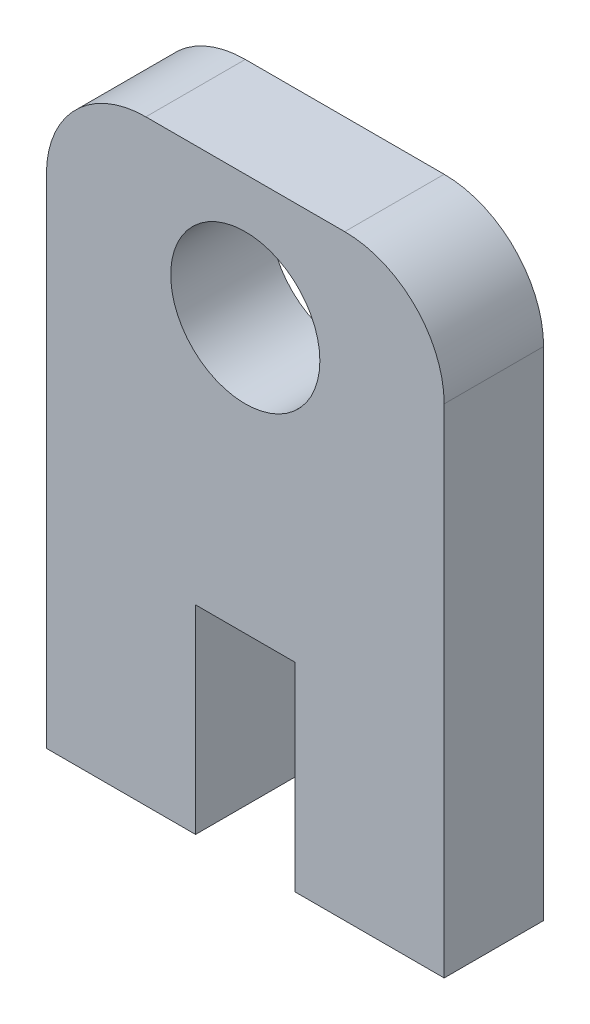
SolidWorks part; units mm, degrees
ref_plane "Front Plane" through (0, 0, 0) normal (0, 0, 1) x (1, 0, 0)
ref_plane "Top Plane" through (0, 0, 0) normal (0, 1, 0) x (1, 0, 0)
ref_plane "Right Plane" through (0, 0, 0) normal (1, 0, 0) x (0, 0, -1)
sketch "Sketch1" plane through (0, 0, 0) normal (0, 0, 1) x (1, 0, 0)
  line L0 (172.8663, -7.9375) -> (172.8663, 3.175) construction
  line L1 (176.0413, -1.5875) -> (182.3913, -1.5875)
  line L2 (172.8663, -4.7625) -> (172.8663, -20.6375)
  line L3 (172.8663, -20.6375) -> (185.5663, -20.6375)
  line L4 (185.5663, -4.7625) -> (185.5663, -20.6375)
  line L5 (133.9995, 0) -> (191.9163, 0) construction
  line L7 (177.6288, -20.6375) -> (180.8038, -20.6375)
  line L8 (177.6288, -20.6375) -> (177.6288, -14.2875)
  line L9 (177.6288, -14.2875) -> (180.8038, -14.2875)
  line L10 (180.8038, -20.6375) -> (180.8038, -14.2875)
  circle A0 centre (179.2163, -5.5562) radius 2.3813
  arc A1 (182.3913, -1.5875) -> (185.5663, -4.7625) centre (182.3913, -4.7625) cw
  arc A2 (176.0413, -1.5875) -> (172.8663, -4.7625) centre (176.0413, -4.7625) ccw
  point P17 (185.5663, -1.5875)
  point P20 (172.8663, -1.5875)
  dimension "D7" = 3.175
  dimension "D1" = 12.7
  dimension "D2" = 1.5875
  dimension "D3" = 19.05
  dimension "D4" = 3.175
  dimension "D5" = 4.7625
  dimension "D6" = 6.35
extrude "Boss-Extrude1" add sketch "Sketch1" along normal blind 3.175 contours L1 A2 L2 L3 L8 L9 L10 L4 A1 A0
